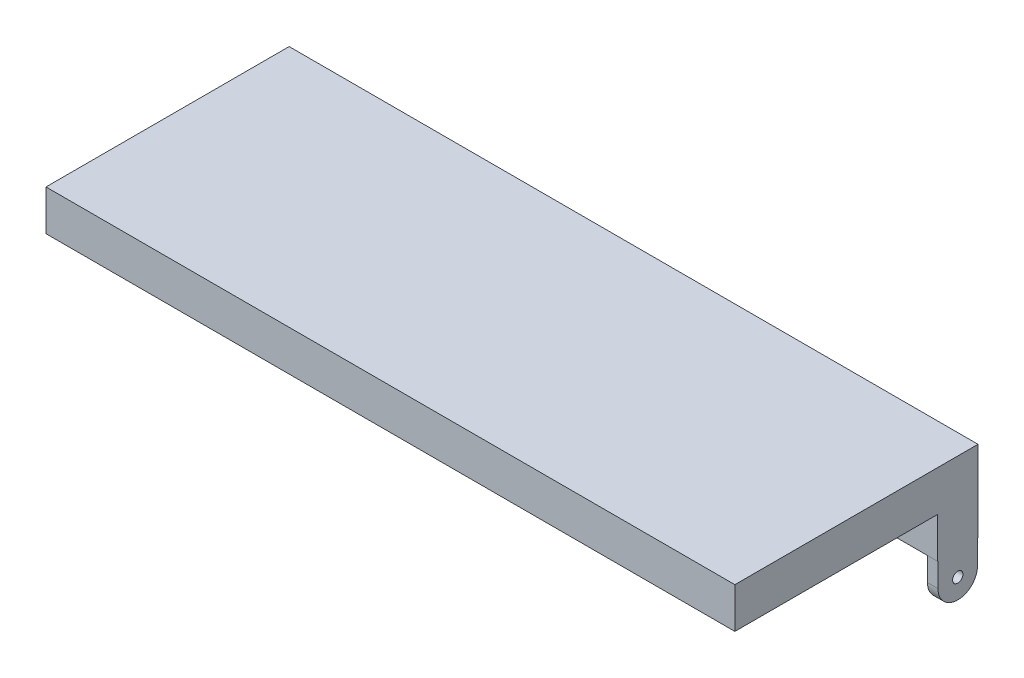
SolidWorks part; units mm, degrees
ref_plane "Front Plane" through (0, 0, 0) normal (0, 0, 1) x (1, 0, 0)
ref_plane "Top Plane" through (0, 0, 0) normal (0, 1, 0) x (1, 0, 0)
ref_plane "Right Plane" through (0, 0, 0) normal (1, 0, 0) x (0, 0, -1)
sketch "Sketch1" plane through (0, 0, 0) normal (0, 1, 0) x (1, 0, 0)
  line L1 (0, 0) -> (85, 0)
  line L2 (0, 0) -> (0, 30)
  line L3 (0, 30) -> (85, 30)
  line L4 (85, 0) -> (85, 30)
  dimension "D1" = 85
  dimension "D2" = 30
extrude "Top surface" add sketch "Sketch1" along normal blind 10
sketch "Sketch6" plane through (0, 0, 0) normal (-1, 0, 0) x (0, 0, 1)
  line L1 (0, 0) -> (-25, 0)
  line L2 (0, 0) -> (0, 5)
  line L3 (0, 5) -> (-25, 5)
  line L4 (-25, 0) -> (-25, 5)
  dimension "D1" = 5
  dimension "D2" = 25
  dimension "D3" = 25
extrude "Top surface cut" cut sketch "Sketch6" against normal through all
move or copy body "Body-Move/Copy1" bodies to move or copy 102 copy no translate (0, 9.9848, 0)
sketch "Sketch8" plane through (0, 0, 0) normal (-1, 0, 0) x (0, 0, 1)
  line L0 (-27.5, 9.9848) -> (-27.5, 7.0348) construction
  line L1 (-30, 9.9848) -> (-25, 9.9848) construction
  line L2 (-29.94, 7.0348) -> (-29.94, 9.9848)
  line L4 (-25.06, 7.0348) -> (-25.06, 9.9848)
  circle A0 centre (-27.5, 7.0348) radius 0.64
  circle A1 centre (-27.5, 7.0348) radius 2.44
  dimension "D1" = 1.28
  dimension "D2" = 4.88
extrude "Boss-Extrude2" add sketch "Sketch8" against normal blind 1.3
pattern_linear "LPattern2" count 2 spacing 83.7 along (1, 0, 0) of "Boss-Extrude2"
ref_plane "Plane1" through (0, 14.9848, 0) normal (-1, 0, 0) x (0, 0, 1)
ref_plane "Plane2" through (0, 14.9848, 0) normal (-1, 0, 0) x (0, 0, 1)
